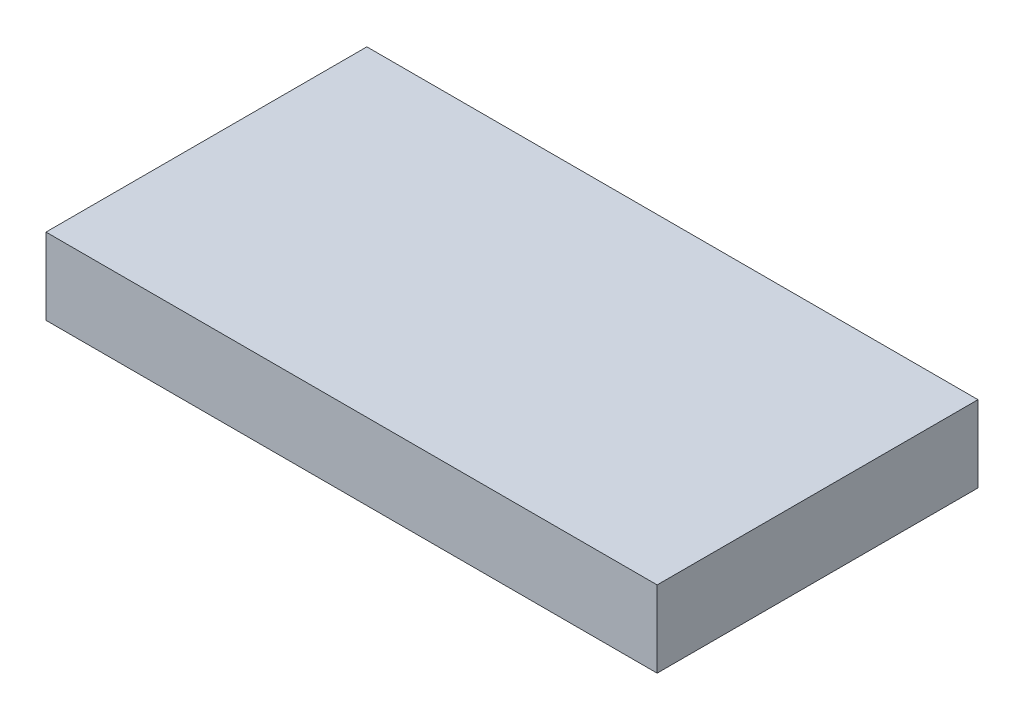
SolidWorks part; units mm, degrees
ref_plane "Front Plane" through (0, 0, 0) normal (0, 0, 1) x (1, 0, 0)
ref_plane "Top Plane" through (0, 0, 0) normal (0, 1, 0) x (1, 0, 0)
ref_plane "Right Plane" through (0, 0, 0) normal (1, 0, 0) x (0, 0, -1)
sketch "Sketch1" plane through (0, 0, 0) normal (0, 1, 0) x (1, 0, 0)
  line L1 (0, 0) -> (101.52, 0)
  line L2 (0, 0) -> (0, 53.3)
  line L3 (0, 53.3) -> (101.52, 53.3)
  line L4 (101.52, 0) -> (101.52, 53.3)
  dimension "D1" = 101.52
  dimension "D2" = 53.3
extrude "Boss-Extrude1" add sketch "Sketch1" along normal blind 12.7
